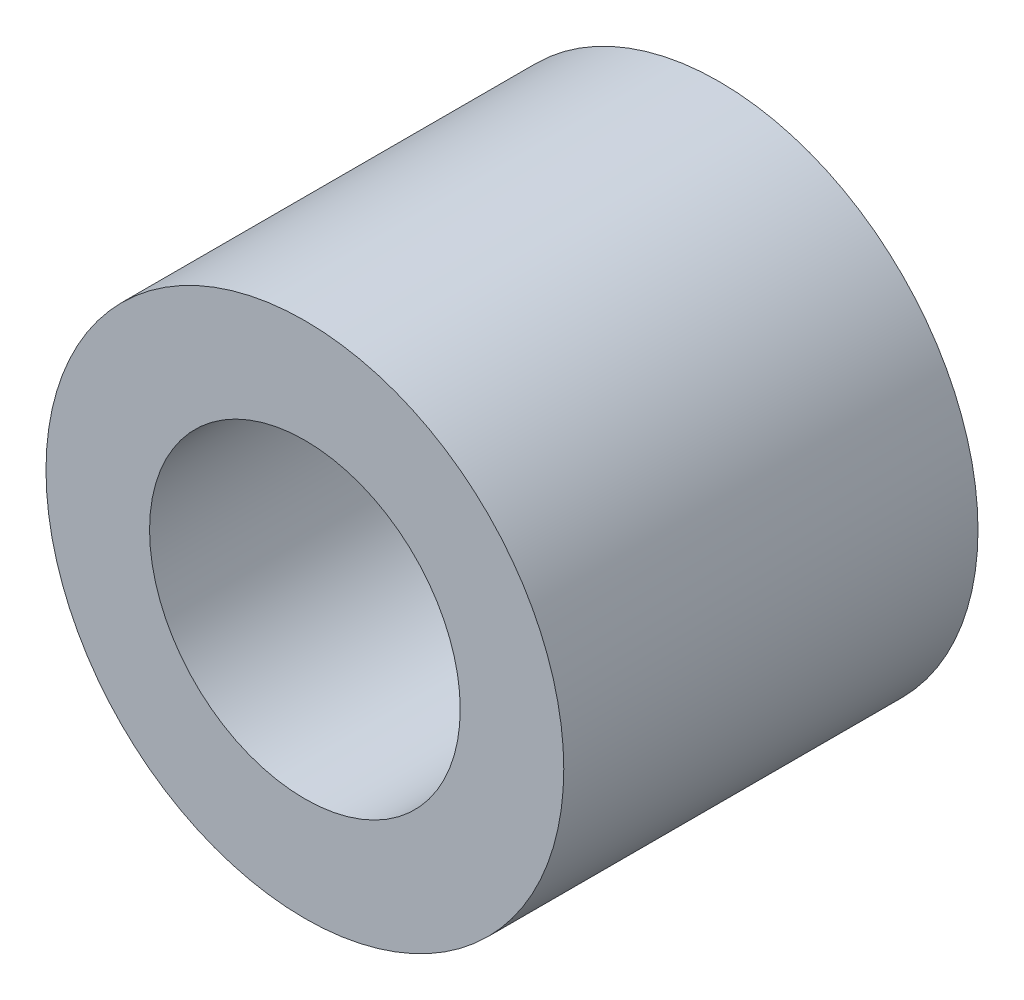
SolidWorks part; units mm, degrees
ref_plane "Front Plane" through (0, 0, 0) normal (0, 0, 1) x (1, 0, 0)
ref_plane "Top Plane" through (0, 0, 0) normal (0, 1, 0) x (1, 0, 0)
ref_plane "Right Plane" through (0, 0, 0) normal (1, 0, 0) x (0, 0, -1)
sketch "Sketch1" plane through (0, 0, 0) normal (0, 0, 1) x (1, 0, 0)
  circle A0 centre (0, 0) radius 3.175
  circle A1 centre (0, 0) radius 1.905
  dimension "D1" = 6.35
  dimension "D2" = 3.81
extrude "Boss-Extrude1" add sketch "Sketch1" along normal blind 5.08
